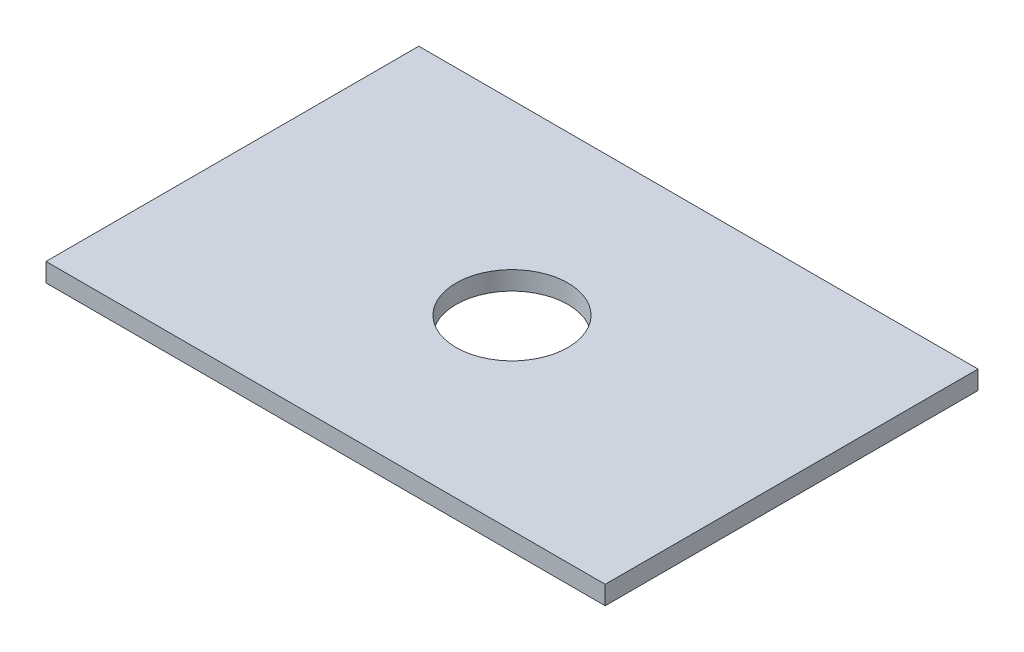
SolidWorks part; units mm, degrees
ref_plane "Alzado" through (0, 0, 0) normal (0, 0, 1) x (1, 0, 0)
ref_plane "Planta" through (0, 0, 0) normal (0, 1, 0) x (1, 0, 0)
ref_plane "Vista lateral" through (0, 0, 0) normal (1, 0, 0) x (0, 0, -1)
sketch "Croquis1" plane through (0, 0, 0) normal (0, 1, 0) x (1, 0, 0)
  line L1 (-150, -100) -> (150, -100)
  line L2 (-150, -100) -> (-150, 100)
  line L3 (-150, 100) -> (150, 100)
  line L4 (150, -100) -> (150, 100)
  line L5 (-150, -100) -> (150, 100) construction
  line L6 (-150, 100) -> (150, -100) construction
  point P0 (0, 0)
  dimension "D1" = 300
  dimension "D2" = 200
extrude "Saliente-Extruir1" add sketch "Croquis1" along normal blind 10
sketch "Croquis2" plane through (0, 10, 0) normal (0, 1, 0) x (1, 0, 0)
  circle A0 centre (0, 0) radius 30
  dimension "D1" = 60
extrude "Cortar-Extruir1" cut sketch "Croquis2" against normal up to surface (10 mm away) up to face at (0, 0, 0)
